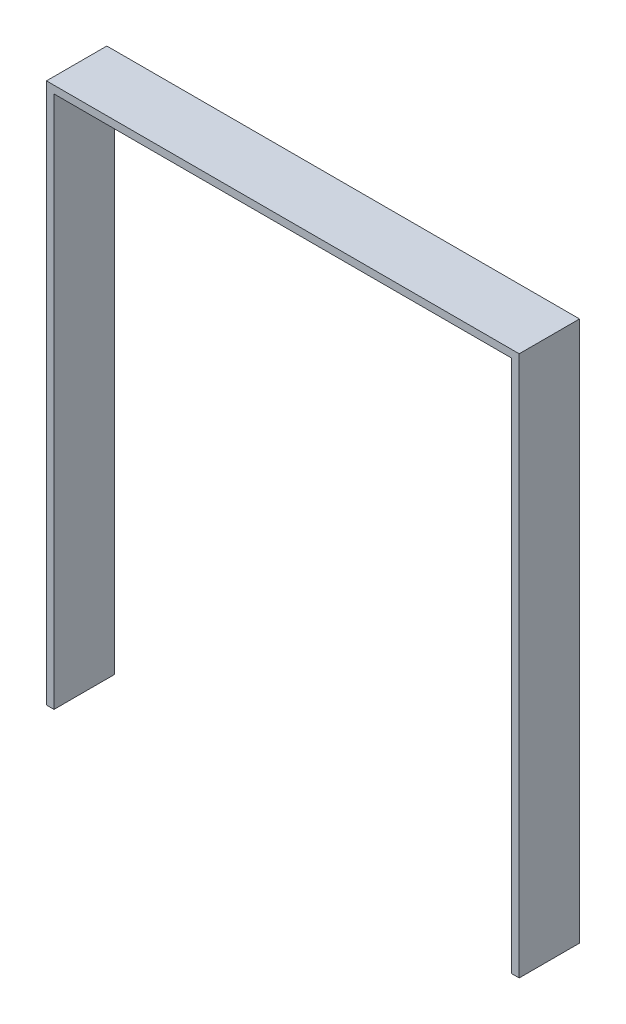
SolidWorks part; units mm, degrees
ref_plane "前视基准面" through (0, 0, 0) normal (0, 0, 1) x (1, 0, 0)
ref_plane "上视基准面" through (0, 0, 0) normal (0, 1, 0) x (1, 0, 0)
ref_plane "右视基准面" through (0, 0, 0) normal (1, 0, 0) x (0, 0, -1)
other "Configuration Table"
sketch "草图1" plane through (0, 0, 0) normal (0, 0, 1) x (1, 0, 0)
  line L0 (-3, 0) -> (-3, 215)
  line L1 (-3, 215) -> (185, 215)
  line L2 (185, 215) -> (185, 0)
  line L3 (185, 0) -> (182, 0)
  line L4 (182, 0) -> (182, 212)
  line L5 (182, 212) -> (0, 212)
  line L6 (0, 212) -> (0, 0)
  line L7 (0, 0) -> (-3, 0)
  dimension "x0" = 3
  dimension "x2" = 185
  dimension "x4" = 182
  dimension "y1" = 215
  dimension "y5" = 212
extrude "Extrude" add sketch "草图1" along normal blind 24
